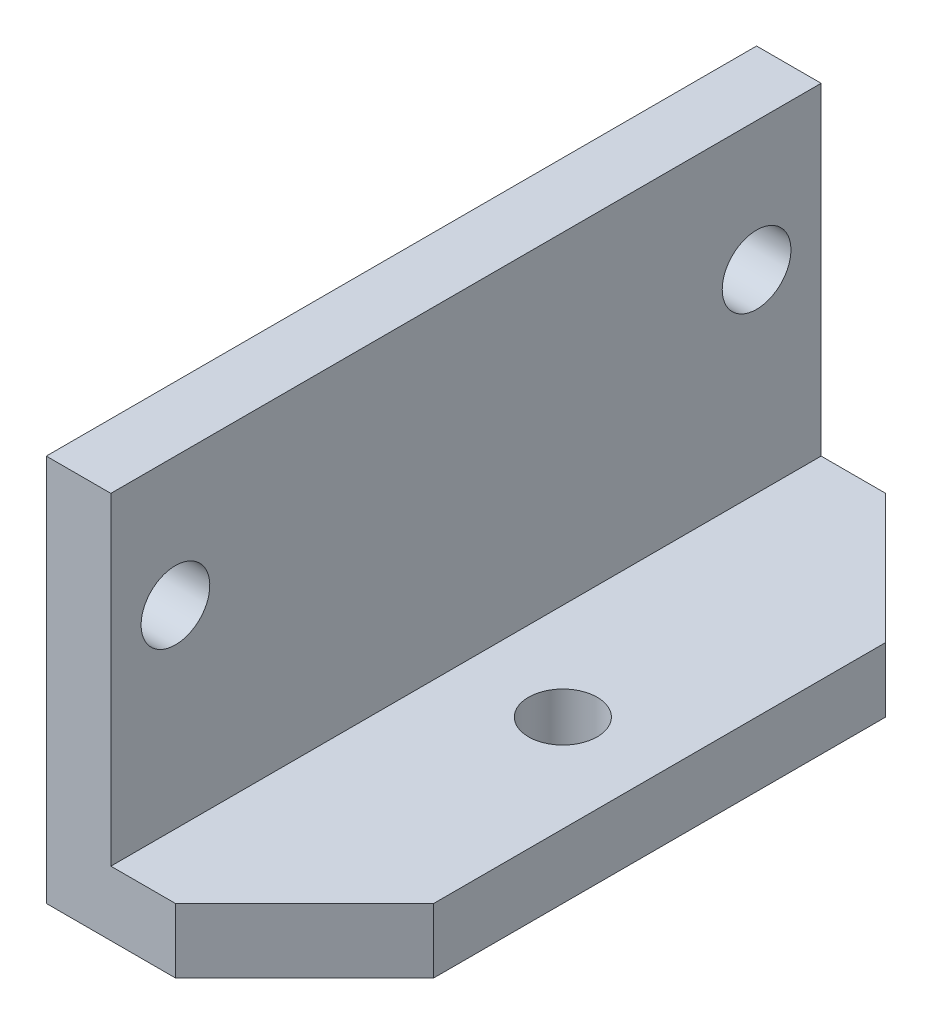
SolidWorks part; units mm, degrees
ref_plane "Front" through (0, 0, 0) normal (0, 0, 1) x (1, 0, 0)
ref_plane "Top" through (0, 0, 0) normal (0, 1, 0) x (1, 0, 0)
ref_plane "Right" through (0, 0, 0) normal (1, 0, 0) x (0, 0, -1)
sketch "Sketch1" plane through (0, 0, 0) normal (0, 0, 1) x (1, 0, 0)
  line L0 (0, 38.1) -> (0, 0)
  line L1 (0, -50) -> (0, 50) construction
  line L2 (0, 0) -> (25.4, 0)
  line L3 (50, 0) -> (-50, 0) construction
  line L4 (25.4, 0) -> (25.4, 6.35)
  line L5 (25.4, 6.35) -> (6.35, 6.35)
  line L6 (6.35, 6.35) -> (6.35, 38.1)
  line L7 (6.35, 38.1) -> (0, 38.1)
  dimension "D1" = 6.35
  dimension "D2" = 38.1
  dimension "D3" = 25.4
extrude "Boss-Extrude1" add sketch "Sketch1" along normal mid plane 69.85
sketch "Sketch2" plane through (0, 0, 0) normal (-1, 0, 0) x (0, 0, 1)
  line L0 (-34.925, 25.4) -> (-28.575, 25.4) construction
  line L1 (-34.925, 38.1) -> (-34.925, 0) construction
  line L2 (-28.575, 25.4) -> (28.575, 25.4) construction
  line L3 (28.575, 25.4) -> (34.925, 25.4) construction
  line L4 (34.925, 38.1) -> (34.925, 0) construction
  line L5 (34.925, 0) -> (-34.925, 0) construction
  dimension "D1" = 57.15
  dimension "D2" = 25.4
hole_wizard "1/4 Clearance Hole1" positions "Sketch4" profile "Sketch3" hole size "1/4" standard "ANSI Inch" end condition through all
sketch "Sketch4" plane through (0, 0, 0) normal (-1, 0, 0) x (0, 0, 1)
  point P0 (-28.575, 25.4)
  point P3 (28.575, 25.4)
sketch "Sketch3" plane through (0, 25.4, -28.575) normal (0, 1, 0) x (0, 0, 1)
  line L0 (0, 0) -> (0, 25.4)
  line L1 (0, 25.4) -> (3.3782, 25.4)
  line L2 (3.3782, 25.4) -> (3.3782, 0)
  line L5 (3.3782, 0) -> (0, 0)
  line L11 (0, -6.35) -> (0, 107.95) construction
  dimension "Thru Hole Dia." = 6.7564
  dimension "Thru Hole Depth" = 25.4
sketch "Sketch5" plane through (0, 6.35, 0) normal (0, 1, 0) x (1, 0, 0)
  line L0 (6.35, 0) -> (15.875, 0) construction
  line L1 (6.35, -34.925) -> (6.35, 34.925) construction
  dimension "D1" = 9.525
hole_wizard "1/4 Clearance Hole2" positions "Sketch7" profile "Sketch6" hole size "1/4" standard "ANSI Inch" end condition through all
sketch "Sketch7" plane through (0, 6.35, 0) normal (0, 1, 0) x (1, 0, 0)
  point P0 (15.875, 0)
sketch "Sketch6" plane through (15.875, 6.35, 0) normal (1, 0, 0) x (0, 0, 1)
  line L0 (0, 0) -> (0, 6.35)
  line L1 (0, 6.35) -> (3.3782, 6.35)
  line L2 (3.3782, 6.35) -> (3.3782, 0)
  line L5 (3.3782, 0) -> (0, 0)
  line L11 (0, -6.35) -> (0, 107.95) construction
  dimension "Thru Hole Dia." = 6.7564
  dimension "Thru Hole Depth" = 6.35
chamfer "Chamfer1" distance 12.7 angle 45 2 edges at (25.4, 3.175, -34.925) (25.4, 3.175, 34.925)
